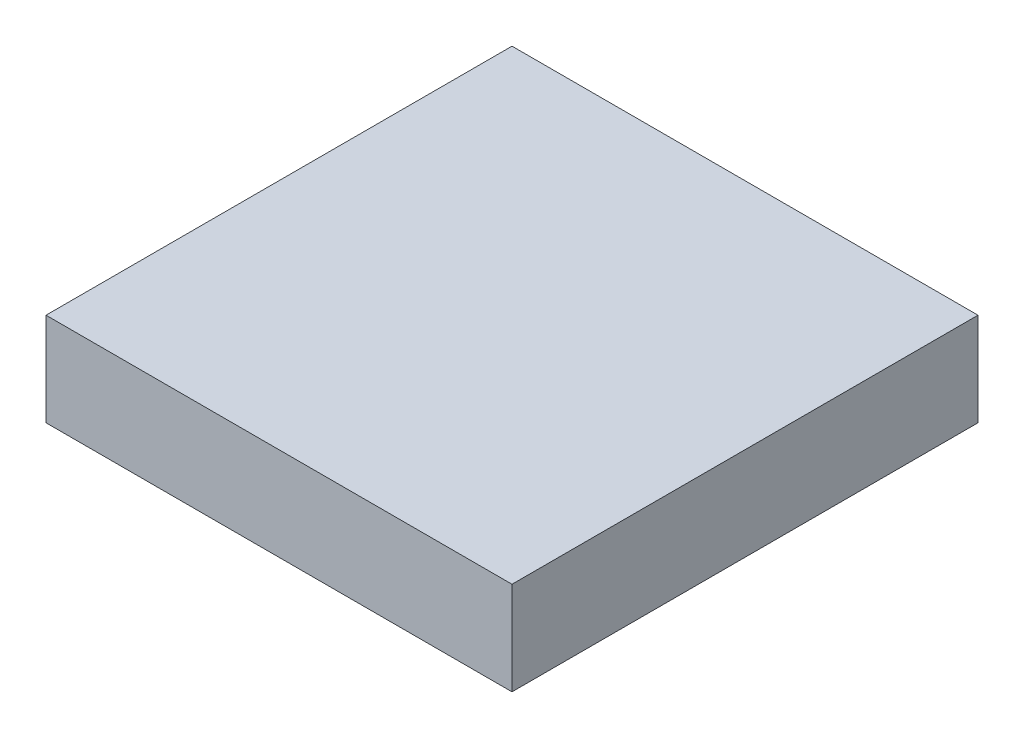
SolidWorks part; units mm, degrees
ref_plane "Front Plane" through (0, 0, 0) normal (0, 0, 1) x (1, 0, 0)
ref_plane "Top Plane" through (0, 0, 0) normal (0, 1, 0) x (1, 0, 0)
ref_plane "Right Plane" through (0, 0, 0) normal (1, 0, 0) x (0, 0, -1)
sketch "Sketch1" plane through (0, 0, 0) normal (0, 1, 0) x (1, 0, 0)
  line L1 (-5, -5) -> (5, -5)
  line L2 (-5, -5) -> (-5, 5)
  line L3 (-5, 5) -> (5, 5)
  line L4 (5, -5) -> (5, 5)
  line L5 (-5, -5) -> (5, 5) construction
  line L6 (-5, 5) -> (5, -5) construction
  point P0 (0, 0)
  dimension "D1" = 10
  dimension "D2" = 10
extrude "Boss-Extrude1" add sketch "Sketch1" along normal blind 2
